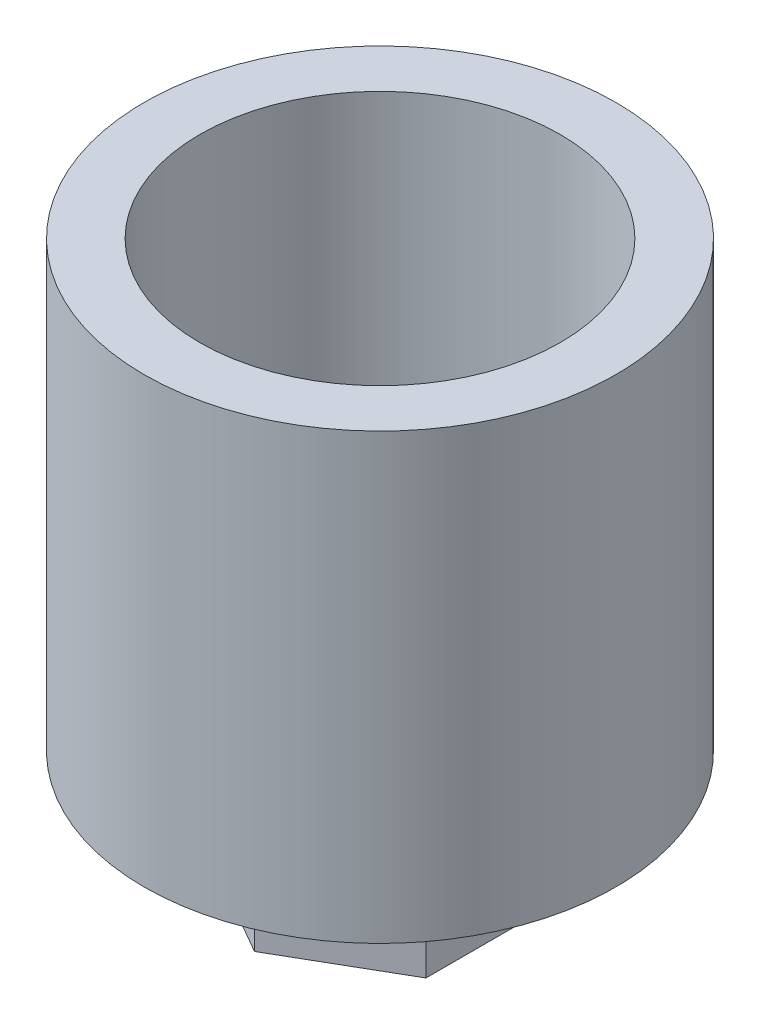
SolidWorks part; units mm, degrees
material "AISI 304"
ref_plane "Front Plane" through (0, 0, 0) normal (0, 0, 1) x (1, 0, 0)
ref_plane "Top Plane" through (0, 0, 0) normal (0, 1, 0) x (1, 0, 0)
ref_plane "Right Plane" through (0, 0, 0) normal (1, 0, 0) x (0, 0, -1)
sketch "Sketch1" plane through (0, 0, 0) normal (0, 1, 0) x (1, 0, 0)
  circle A0 centre (0, 0) radius 13.5
  dimension "D1" = 27
extrude "Boss-Extrude1" add sketch "Sketch1" along normal blind 25.4
hole_wizard "7/8-14 Tapped Hole1" positions "Sketch4" profile "Sketch5" tap size "7/8-14" standard "ANSI Inch"
sketch "Sketch4" plane through (0, 25.4, 0) normal (0, 1, 0) x (1, 0, 0)
  point P0 (0, 0)
sketch "Sketch5" plane through (0, 25.4, 0) normal (1, 0, 0) x (0, 0, 1)
  line L0 (0, 0) -> (0, 25.2501)
  line L1 (0, 25.2501) -> (10.3187, 19.05)
  line L2 (10.3187, 19.05) -> (10.3187, 0)
  line L5 (10.3187, 0) -> (0, 0)
  line L10 (0, 25.2501) -> (-10.3188, 19.05) construction
  line L11 (0, -6.35) -> (0, 107.95) construction
  dimension "Tap Drill Dia." = 20.6375
  dimension "Tap Drill Depth" = 19.05
  dimension "Drill Angle" = 118
cosmetic thread "Hole Thread1" parameters "D1"=44.45, "D2"=22.225
sketch "Sketch6" plane through (0, 0, 0) normal (0, -1, 0) x (1, 0, 0)
  line L1 (6.223, 3.5929) -> (0, 7.1857)
  line L2 (0, 7.1857) -> (-6.223, 3.5929)
  line L3 (-6.223, 3.5929) -> (-6.223, -3.5929)
  line L4 (-6.223, -3.5929) -> (0, -7.1857)
  line L5 (0, -7.1857) -> (6.223, -3.5929)
  line L6 (6.223, -3.5929) -> (6.223, 3.5929)
  circle A0 centre (0, 0) radius 6.223 construction
  dimension "D1" = 12.446
extrude "Boss-Extrude2" add sketch "Sketch6" along normal blind 6.35
